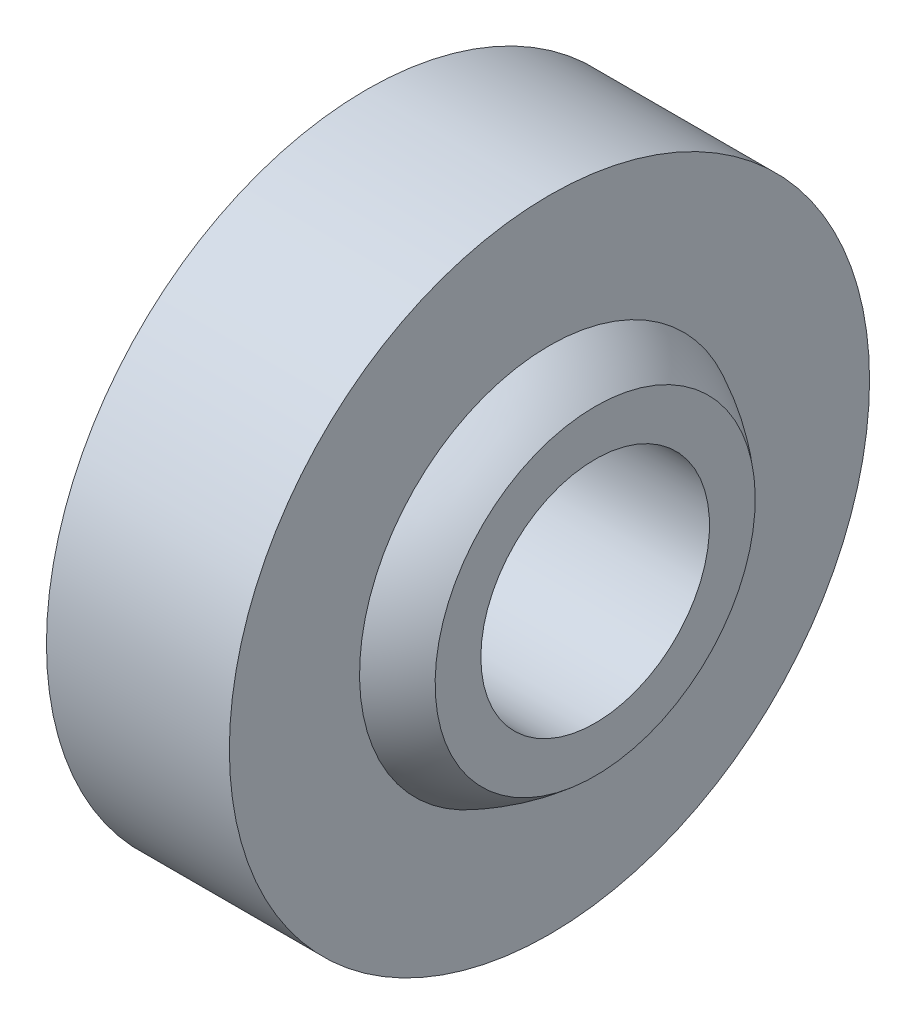
SolidWorks part; units mm, degrees
material "合金钢"
ref_plane "前视基准面" through (0, 0, 0) normal (0, 0, 1) x (1, 0, 0)
ref_plane "上视基准面" through (0, 0, 0) normal (0, 1, 0) x (1, 0, 0)
ref_plane "右视基准面" through (0, 0, 0) normal (1, 0, 0) x (0, 0, -1)
other "Configuration Table"
sketch "草图1" plane through (0, 0, 0) normal (0, 0, 1) x (1, 0, 0)
  line L0 (-2.9558, 0) -> (2.3907, 0) construction
  line L1 (0, 1.717) -> (0, -2.3038) construction
  line L2 (-3, 2.5) -> (3, 2.5)
  line L3 (-3, 3.5) -> (-3, 2.5)
  line L4 (3, 3.5) -> (3, 2.5)
  arc A0 (3, 3.5) -> (-3, 3.5) centre (0, 0) ccw
  point P12 (0, 2.5)
  dimension "D1" = 7
  dimension "D2" = 5
  dimension "D3" = 6
revolve "旋转1" add sketch "草图1" angle 360 about L0
sketch "草图3" plane through (0, 0, 0) normal (0, 0, 1) x (1, 0, 0)
  line L0 (0, 6.3041) -> (0, 2.2339) construction
  line L1 (-2, 7) -> (2, 7)
  line L2 (-2, 7) -> (-2, 4.1533)
  line L3 (-2, 4.1533) -> (2, 4.1533)
  line L4 (2, 7) -> (2, 4.1533)
  line L5 (-4.3558, 0) -> (8.3455, 0) construction
  arc A0 (3, 3.5) -> (-3, 3.5) centre (0, 0) ccw construction
  dimension "D1" = 4
  dimension "D2" = 7
revolve "旋转2" add sketch "草图3" angle 360 about L5
